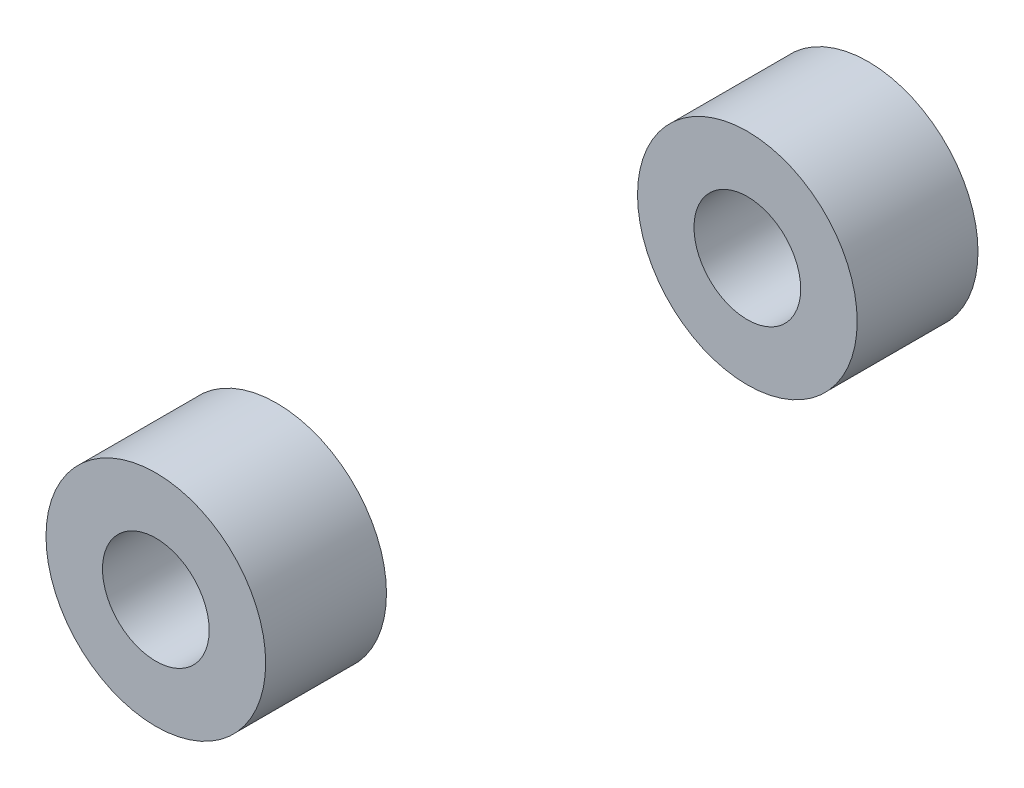
SolidWorks part; units mm, degrees
ref_plane "前视基准面" through (0, 0, 0) normal (0, 0, 1) x (1, 0, 0)
ref_plane "上视基准面" through (0, 0, 0) normal (0, 1, 0) x (1, 0, 0)
ref_plane "右视基准面" through (0, 0, 0) normal (1, 0, 0) x (0, 0, -1)
sketch "草图1" plane through (0, 0, 0) normal (0, 0, 1) x (1, 0, 0)
  circle A0 centre (0, 0) radius 3.5
  circle A1 centre (0, 0) radius 1.7
  dimension "D1" = 7
  dimension "D2" = 3.4
extrude "凸台-拉伸1" add sketch "草图1" along normal blind 22.7
ref_plane "基准面1" through (0, 0, 11.35) normal (0, 0, 1) x (1, 0, 0)
sketch "草图2" plane through (0, 0, 11.35) normal (0, 0, 1) x (1, 0, 0)
  circle A0 centre (0, 0) radius 3.5 construction
  circle A1 centre (0, 0) radius 3.5
extrude "切除-拉伸1" cut sketch "草图2" against normal mid plane 15
